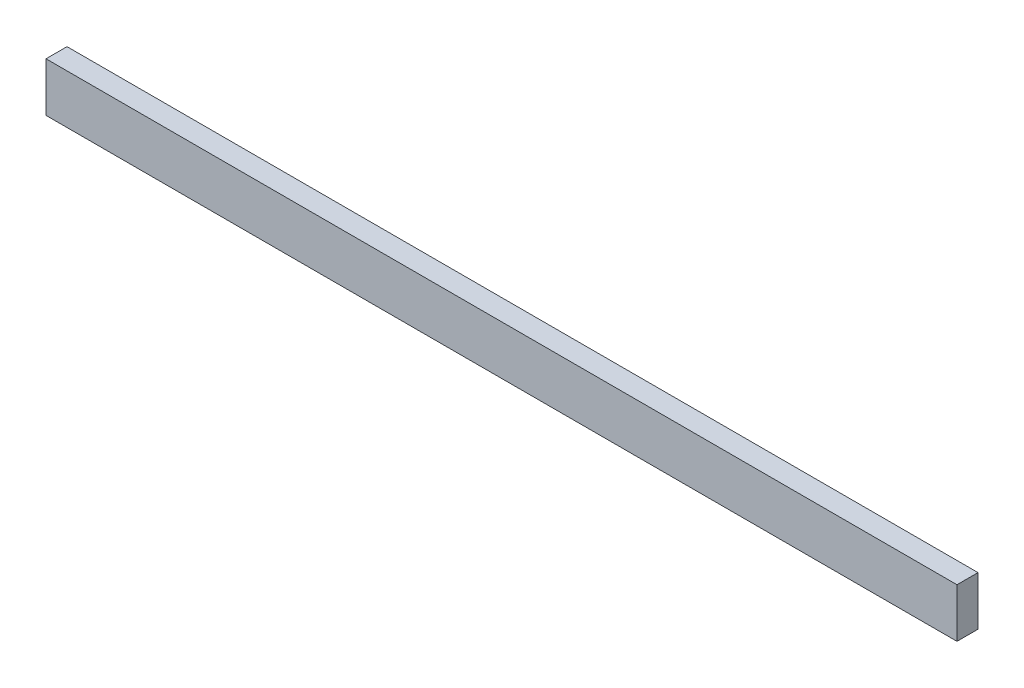
SolidWorks part; units mm, degrees
ref_plane "前视基准面" through (0, 0, 0) normal (0, 0, 1) x (1, 0, 0)
ref_plane "上视基准面" through (0, 0, 0) normal (0, 1, 0) x (1, 0, 0)
ref_plane "右视基准面" through (0, 0, 0) normal (1, 0, 0) x (0, 0, -1)
other "Configuration Table"
sketch "草图1" plane through (0, 0, 0) normal (0, 0, 1) x (1, 0, 0)
  line L0 (0, 0) -> (650, 0)
  line L1 (650, 0) -> (650, 35)
  line L2 (650, 35) -> (0, 35)
  line L3 (0, 35) -> (0, 0)
  dimension "width" = 650
  dimension "height" = 35
extrude "BlockExtrude" add sketch "草图1" along normal blind 15
